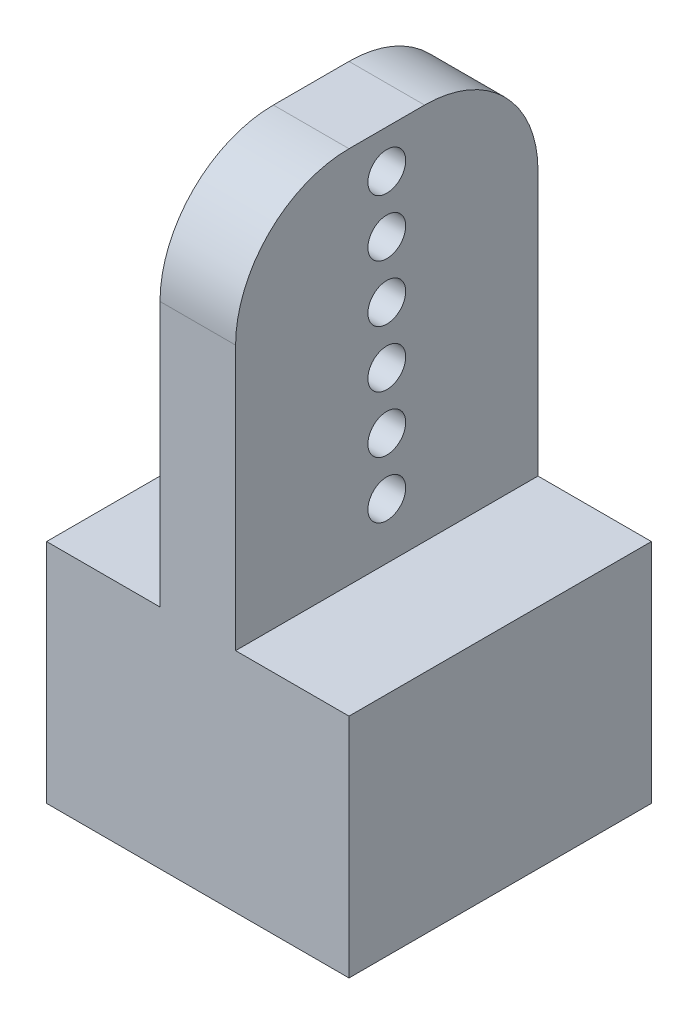
SolidWorks part; units mm, degrees
material "ABS"
ref_plane "Front Plane" through (0, 0, 0) normal (0, 0, 1) x (1, 0, 0)
ref_plane "Top Plane" through (0, 0, 0) normal (0, 1, 0) x (1, 0, 0)
ref_plane "Right Plane" through (0, 0, 0) normal (1, 0, 0) x (0, 0, -1)
sketch "Sketch1" plane through (0, 0, 0) normal (0, 1, 0) x (1, 0, 0)
  line L1 (-10, 10) -> (10, 10)
  line L2 (-10, 10) -> (-10, -10)
  line L3 (-10, -10) -> (10, -10)
  line L4 (10, 10) -> (10, -10)
  line L5 (-10, 10) -> (10, -10) construction
  line L6 (-10, -10) -> (10, 10) construction
  line L7 (-20, 20) -> (20, 20)
  line L8 (-20, 20) -> (-20, -20)
  line L9 (-20, -20) -> (20, -20)
  line L10 (20, 20) -> (20, -20)
  line L11 (-20, 20) -> (20, -20) construction
  line L12 (-20, -20) -> (20, 20) construction
  point P0 (0, 0)
  point P6 (0, 0)
  dimension "D1" = 20
  dimension "D2" = 20
  dimension "D3" = 40
  dimension "D4" = 40
extrude "Boss-Extrude1" add sketch "Sketch1" along normal blind 30 contours L4 L1 L2 L3 | L10 L7 L8 L9 L1 L4 L3 L2
sketch "Sketch4" plane through (0, 30, 0) normal (0, 1, 0) x (1, 0, 0)
  line L1 (-5, -20) -> (5, -20)
  line L2 (-5, -20) -> (-5, 20)
  line L3 (-5, 20) -> (5, 20)
  line L4 (5, -20) -> (5, 20)
  line L5 (-5, -20) -> (5, 20) construction
  line L6 (-5, 20) -> (5, -20) construction
  line L7 (-20, 20) -> (20, 20) construction
  point P0 (0, 0)
  dimension "D1" = 10
extrude "Boss-Extrude3" add sketch "Sketch4" along normal blind 50
sketch "Sketch5" plane through (5, 0, 0) normal (1, 0, 0) x (0, 0, -1)
  circle A0 centre (0, 37.4072) radius 2.5
  dimension "D1" = 5
extrude "Cut-Extrude4" cut sketch "Sketch5" against normal through all
pattern_linear "LPattern1" count 6 spacing 7.5 along (0, 1, 0) of "Cut-Extrude4"
fillet "Fillet1" radius 15 2 edges at (0, 80, -20) (0, 80, 20)
sketch "Sketch6" plane through (0, 0, -20) normal (0, 0, -1) x (-1, 0, 0)
  line L1 (-15, 26) -> (15, 26)
  line L2 (-15, 26) -> (-15, 4)
  line L3 (-15, 4) -> (15, 4)
  line L4 (15, 26) -> (15, 4)
  line L5 (-15, 26) -> (15, 4) construction
  line L6 (-15, 4) -> (15, 26) construction
  point P0 (0, 15)
  dimension "D1" = 30
  dimension "D2" = 22
extrude "Cut-Extrude5" cut sketch "Sketch6" against normal blind 30
sketch "Sketch7" plane through (0, 0, 0) normal (0, -1, 0) x (1, 0, 0)
  line L0 (20, -20) -> (20, 20) construction
  circle A0 centre (-7.5, -2) radius 2.75
  circle A1 centre (7.5, -2) radius 2.75
  dimension "D1" = 5.5
  dimension "D2" = 5.5
  dimension "D3" = 22
  dimension "D4" = 15
  dimension "D5" = 12.5
extrude "Cut-Extrude6" cut sketch "Sketch7" against normal up to next
